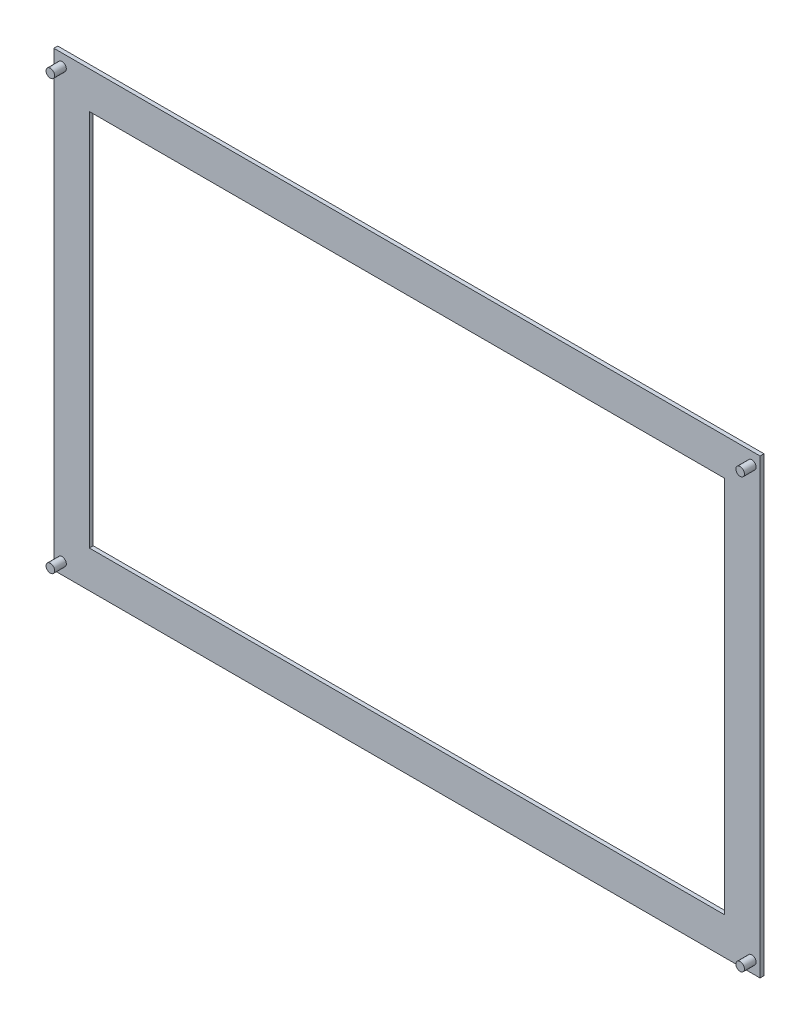
SolidWorks part; units mm, degrees
ref_plane "前视基准面" through (0, 0, 0) normal (0, 0, 1) x (1, 0, 0)
ref_plane "上视基准面" through (0, 0, 0) normal (0, 1, 0) x (1, 0, 0)
ref_plane "右视基准面" through (0, 0, 0) normal (1, 0, 0) x (0, 0, -1)
sketch "草图1" plane through (0, 0, 0) normal (0, 0, 1) x (1, 0, 0)
  line L1 (-90.6, 58) -> (90.6, 58)
  line L2 (-90.6, 58) -> (-90.6, -58)
  line L3 (-90.6, -58) -> (90.6, -58)
  line L4 (90.6, 58) -> (90.6, -58)
  line L5 (-90.6, 58) -> (90.6, -58) construction
  line L6 (-90.6, -58) -> (90.6, 58) construction
  point P0 (0, 0)
  dimension "D1" = 181.2
  dimension "D2" = 116
extrude "凸台-拉伸1" add sketch "草图1" along normal blind 1
sketch "草图2" plane through (0, 0, 1) normal (0, 0, 1) x (1, 0, 0)
  line L1 (-81.5, 48.5) -> (81.5, 48.5)
  line L2 (-81.5, 48.5) -> (-81.5, -48.5)
  line L3 (-81.5, -48.5) -> (81.5, -48.5)
  line L4 (81.5, 48.5) -> (81.5, -48.5)
  line L5 (-81.5, 48.5) -> (81.5, -48.5) construction
  line L6 (-81.5, -48.5) -> (81.5, 48.5) construction
  point P0 (0, 0)
  dimension "D1" = 163
  dimension "D2" = 97
extrude "切除-拉伸1" cut sketch "草图2" against normal blind 1
sketch "草图3" plane through (0, 0, 1) normal (0, 0, 1) x (1, 0, 0)
  line L1 (88.5, 55) -> (-88.5, 55) construction
  line L2 (88.5, 55) -> (88.5, -55) construction
  line L3 (88.5, -55) -> (-88.5, -55) construction
  line L4 (-88.5, 55) -> (-88.5, -55) construction
  line L5 (88.5, 55) -> (-88.5, -55) construction
  line L6 (88.5, -55) -> (-88.5, 55) construction
  circle A0 centre (-88.5, 55) radius 1.1
  circle A1 centre (-88.5, -55) radius 1.1
  circle A2 centre (88.5, -55) radius 1.1
  circle A3 centre (88.5, 55) radius 1.1
  point P0 (0, 0)
  dimension "D3" = 2.2
  dimension "D1" = 177
  dimension "D2" = 110
extrude "凸台-拉伸2" add sketch "草图3" along normal blind 3
